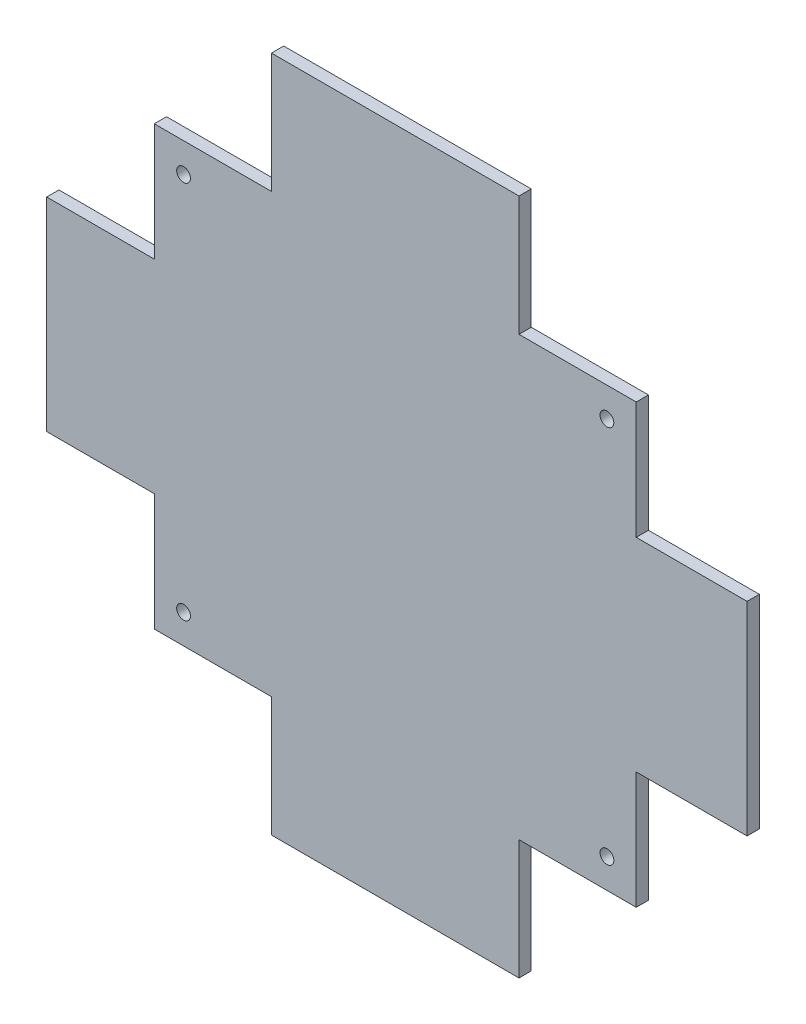
SolidWorks part; units mm, degrees
material "Pin"
ref_plane "Plan de face" through (0, 0, 0) normal (0, 0, 1) x (1, 0, 0)
ref_plane "Plan de dessus" through (0, 0, 0) normal (0, 1, 0) x (1, 0, 0)
ref_plane "Plan de droite" through (0, 0, 0) normal (1, 0, 0) x (0, 0, -1)
sketch "Esquisse1" plane through (0, 0, 0) normal (0, 0, 1) x (1, 0, 0)
  line L0 (55.8, 113.5) -> (116.6, 113.5)
  line L1 (116.6, 113.5) -> (116.6, 175.65)
  line L2 (116.6, 175.65) -> (245, 175.65)
  line L3 (245, 175.65) -> (245, 113.5)
  line L4 (245, 113.5) -> (305.8, 113.5)
  line L5 (305.8, 113.5) -> (305.8, 52.7)
  line L6 (305.8, 52.7) -> (362.1, 52.7)
  line L7 (362.1, 52.7) -> (362.1, -52.7)
  line L8 (362.1, -52.7) -> (305.8, -52.7)
  line L9 (305.8, -52.7) -> (305.8, -113.5)
  line L10 (305.8, -113.5) -> (245, -113.5)
  line L11 (245, -113.5) -> (245, -175.65)
  line L12 (245, -175.65) -> (116.6, -175.65)
  line L13 (116.6, -175.65) -> (116.6, -113.5)
  line L14 (116.6, -113.5) -> (55.8, -113.5)
  line L15 (55.8, -113.5) -> (55.8, -52.7)
  line L16 (55.8, -52.7) -> (0, -52.7)
  line L17 (0, -52.7) -> (0, 52.7)
  line L18 (0, 52.7) -> (55.8, 52.7)
  line L19 (55.8, 52.7) -> (55.8, 113.5)
  dimension "D1" = 105.4
  dimension "D2" = 60.8
  dimension "D3" = 55.8
  dimension "D4" = 62.15
  dimension "D5" = 128.4
  dimension "D6" = 62.15
  dimension "D7" = 128.4
  dimension "D8" = 60.8
  dimension "D9" = 56.3
  dimension "D10" = 60.8
extrude "Boss.-Extru.1" add sketch "Esquisse1" along normal blind 6.35
sketch "Esquisse2" plane through (0, 0, 6.35) normal (0, 0, 1) x (1, 0, 0)
  line L0 (362.1, -52.7) -> (362.1, 52.7) construction
  line L1 (362.1, 52.7) -> (363.3, 52.7)
  line L2 (362.1, 52.7) -> (362.1, -52.7)
  line L3 (362.1, -52.7) -> (363.3, -52.7)
  line L4 (363.3, 52.7) -> (363.3, -52.7)
  line L5 (362.1, 52.7) -> (363.3, -52.7) construction
  line L6 (362.1, -52.7) -> (363.3, 52.7) construction
  point P4 (362.7, 0)
  dimension "D1" = 1.2
extrude "Boss.-Extru.2" add sketch "Esquisse2" against normal through all
hole_wizard "Dégagement 1/41" positions "Esquisse3" profile "Esquisse4" hole size "1/4" standard "Ansi Inch" end condition through all
sketch "Esquisse3" plane through (0, 0, 0) normal (0, 0, -1) x (-1, 0, 0)
  line L0 (-71, 98.3) -> (-290.6, 98.3) construction
  line L1 (-290.6, 98.3) -> (-290.6, -98.3) construction
  line L2 (-290.6, -98.3) -> (-71, -98.3) construction
  line L3 (-71, -98.3) -> (-71, 98.3) construction
  point P0 (-290.6, 98.3)
  point P2 (-71, 98.3)
  point P4 (-71, -98.3)
  point P6 (-290.6, -98.3)
  point P19 (-71, 0)
  dimension "D1" = 219.6
  dimension "D2" = 196.6
  dimension "D3" = 71
sketch "Esquisse4" plane through (290.6, 98.3, 0) normal (1, 0, 0) x (0, 1, 0)
  line L0 (0, 0) -> (0, 6.35)
  line L1 (0, 6.35) -> (3.5712, 6.35)
  line L2 (3.5712, 6.35) -> (3.5712, 0)
  line L5 (3.5712, 0) -> (0, 0)
  line L11 (0, -6.35) -> (0, 107.95) construction
  dimension "Diamètre du perçage jusqu'au prochain" = 7.1425
  dimension "Profondeur du perçage jusqu'au prochain" = 6.35
